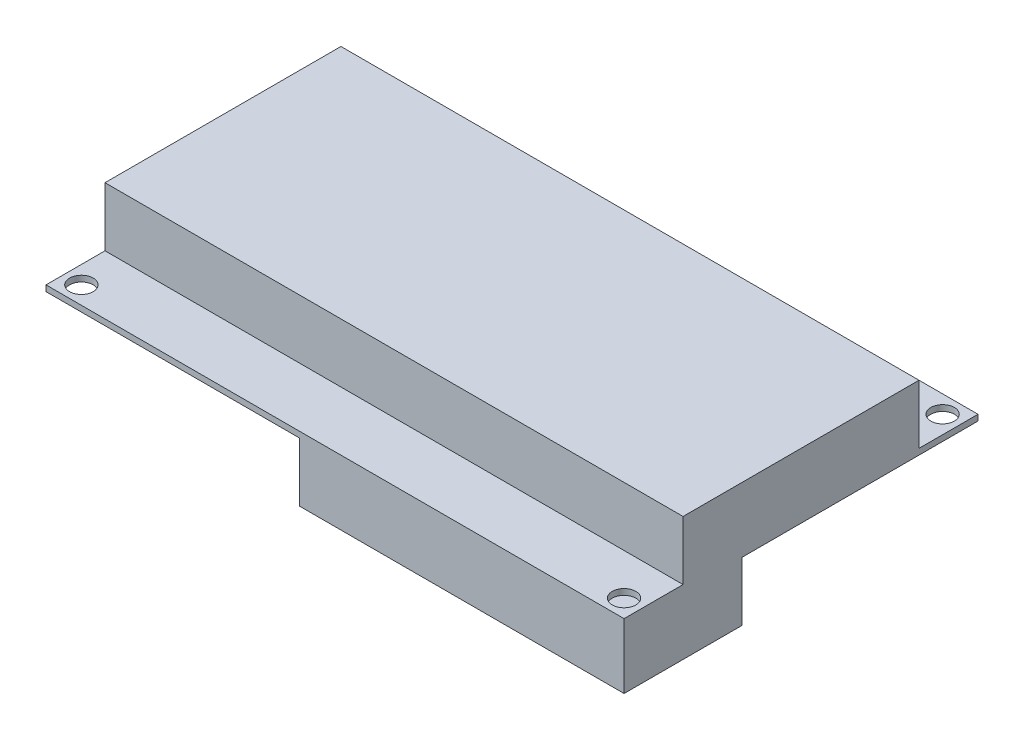
SolidWorks part; units mm, degrees
ref_plane "Front Plane" through (0, 0, 0) normal (0, 0, 1) x (1, 0, 0)
ref_plane "Top Plane" through (0, 0, 0) normal (0, 1, 0) x (1, 0, 0)
ref_plane "Right Plane" through (0, 0, 0) normal (1, 0, 0) x (0, 0, -1)
sketch "Sketch2" plane through (0, 0, 0) normal (0, 1, 0) x (1, 0, 0)
  line L1 (49, -30) -> (-49, -30)
  line L2 (49, -30) -> (49, 30)
  line L3 (49, 30) -> (-49, 30)
  line L4 (-49, -30) -> (-49, 30)
  line L5 (49, -30) -> (-49, 30) construction
  line L6 (49, 30) -> (-49, -30) construction
  point P0 (0, 0)
  dimension "D1" = 60
  dimension "D2" = 98
extrude "Boss-Extrude1" add sketch "Sketch2" along normal blind 1
sketch "Sketch3" plane through (0, 1, 0) normal (0, 1, 0) x (1, 0, 0)
  line L0 (-49, 30) -> (-49, -30) construction
  line L1 (49, -20) -> (-49, -20)
  line L2 (49, -20) -> (49, 20)
  line L3 (49, 20) -> (-49, 20)
  line L4 (-49, -20) -> (-49, 20)
  line L5 (49, -20) -> (-49, 20) construction
  line L6 (49, 20) -> (-49, -20) construction
  point P0 (0, 0)
  dimension "D2" = 40
extrude "Boss-Extrude2" add sketch "Sketch3" along normal blind 10
sketch "Sketch4" plane through (0, 1, 0) normal (0, 1, 0) x (1, 0, 0)
  line L0 (-49, 30) -> (-49, 20) construction
  line L1 (49, 30) -> (-49, 30) construction
  circle A0 centre (-46, 27) radius 2
  dimension "D1" = 4
  dimension "D2" = 3
  dimension "D3" = 3
extrude "Cut-Extrude1" cut sketch "Sketch4" against normal blind 10
mirror "Mirror1" about plane through (0, 0, 0) normal (0, 0, 1) of "Cut-Extrude1"
mirror "Mirror2" about plane through (0, 0, 0) normal (1, 0, 0) of "Mirror1", "Cut-Extrude1"
sketch "Sketch5" plane through (0, 0, 0) normal (0, -1, 0) x (1, 0, 0)
  line L1 (49, 30) -> (-6, 30)
  line L2 (49, 30) -> (49, 10)
  line L3 (49, 10) -> (-6, 10)
  line L4 (-6, 30) -> (-6, 10)
  dimension "D1" = 55
  dimension "D2" = 20
extrude "Boss-Extrude3" add sketch "Sketch5" along normal blind 10
